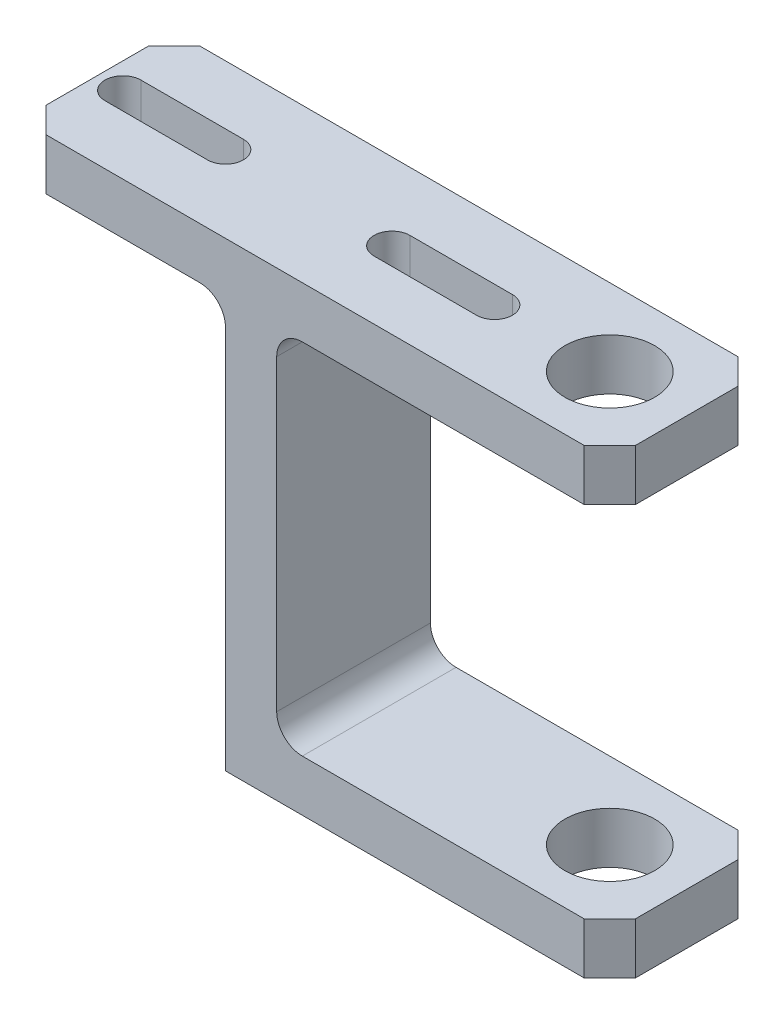
SolidWorks part; units mm, degrees
ref_plane "Front Plane" through (0, 0, 0) normal (0, 0, 1) x (1, 0, 0)
ref_plane "Top Plane" through (0, 0, 0) normal (0, 1, 0) x (1, 0, 0)
ref_plane "Right Plane" through (0, 0, 0) normal (1, 0, 0) x (0, 0, -1)
sketch "Sketch1" plane through (0, 0, 0) normal (0, 0, 1) x (1, 0, 0)
  line L0 (0, 150) -> (0, 0)
  line L1 (0, 0) -> (150, 0)
  line L2 (150, 0) -> (150, 20)
  line L3 (150, 20) -> (30, 20)
  line L4 (20, 30) -> (20, 150)
  line L5 (30, 160) -> (150, 160)
  line L6 (150, 160) -> (150, 180)
  line L7 (150, 180) -> (-80, 180)
  line L8 (-80, 180) -> (-80, 160)
  line L9 (-80, 160) -> (-10, 160)
  arc A0 (0, 150) -> (-10, 160) centre (-10, 150) ccw
  arc A1 (30, 160) -> (20, 150) centre (30, 150) ccw
  arc A2 (20, 30) -> (30, 20) centre (30, 30) ccw
  dimension "D7" = 10
  dimension "D8" = 10
  dimension "D9" = 10
  dimension "D1" = 150
  dimension "D2" = 80
  dimension "D3" = 20
  dimension "D4" = 180
  dimension "D5" = 20
  dimension "D6" = 20
extrude "Boss-Extrude1" add sketch "Sketch1" along normal mid plane 60 contours L0 L1 L2 L3 A2 L4 A1 L5 L6 L7 L8 L9 A0
chamfer "Chamfer1" distance 10 angle 45 1 edges at (150, 170, 30)
chamfer "Chamfer2" distance 10 angle 45 5 edges at (-80, 170, -30) (-80, 170, 30) (150, 10, 30) (150, 10, -30) (150, 170, -30)
sketch "Sketch2" plane through (0, 180, 0) normal (0, 1, 0) x (1, 0, 0)
  line L0 (-30, 7) -> (-70, 7)
  line L1 (-70, -7) -> (-30, -7)
  line L2 (75, 7) -> (35, 7)
  line L3 (35, -7) -> (75, -7)
  line L4 (150, -20) -> (150, 20) construction
  circle A0 centre (120, 0) radius 17.5
  arc A1 (-70, 7) -> (-70, -7) centre (-70, 0) ccw
  arc A2 (-30, 7) -> (-30, -7) centre (-30, 0) cw
  arc A3 (35, 7) -> (35, -7) centre (35, 0) ccw
  arc A4 (75, 7) -> (75, -7) centre (75, 0) cw
  point P14 (0, 0)
  point P16 (77.1581, 1.7705)
  point P17 (146.8485, 0.6815)
  point P19 (0, 0)
  point P21 (0, 0)
  point P22 (0, 0)
  dimension "D1" = 35
  dimension "D2" = 7
  dimension "D3" = 7
  dimension "D4" = 7
  dimension "D5" = 105
  dimension "D6" = 40
  dimension "D7" = 40
  dimension "D8" = 45
  dimension "D9" = 30
extrude "Cut-Extrude1" cut sketch "Sketch2" against normal blind 212 contours A2 L0 A1 L1 | A0
sketch "Sketch4" plane through (0, 180, 0) normal (0, 1, 0) x (1, 0, 0)
  line L0 (-30, 7) -> (-70, 7)
  line L1 (-70, -7) -> (-30, -7)
  line L2 (75, 7) -> (35, 7)
  line L3 (35, -7) -> (75, -7)
  arc A0 (-70, 7) -> (-70, -7) centre (-70, 0) ccw
  arc A1 (-30, 7) -> (-30, -7) centre (-30, 0) cw
  arc A2 (35, 7) -> (35, -7) centre (35, 0) ccw
  arc A3 (75, 7) -> (75, -7) centre (75, 0) cw
  point P10 (0, 0)
  point P17 (0, 0)
  point P18 (0, 0)
  point P21 (58.5095, -0.1086)
  dimension "D3" = 7
  dimension "D1" = 105
  dimension "D2" = 40
extrude "Cut-Extrude2" cut sketch "Sketch4" against normal blind 111 contours L3 A3 L2 A2
